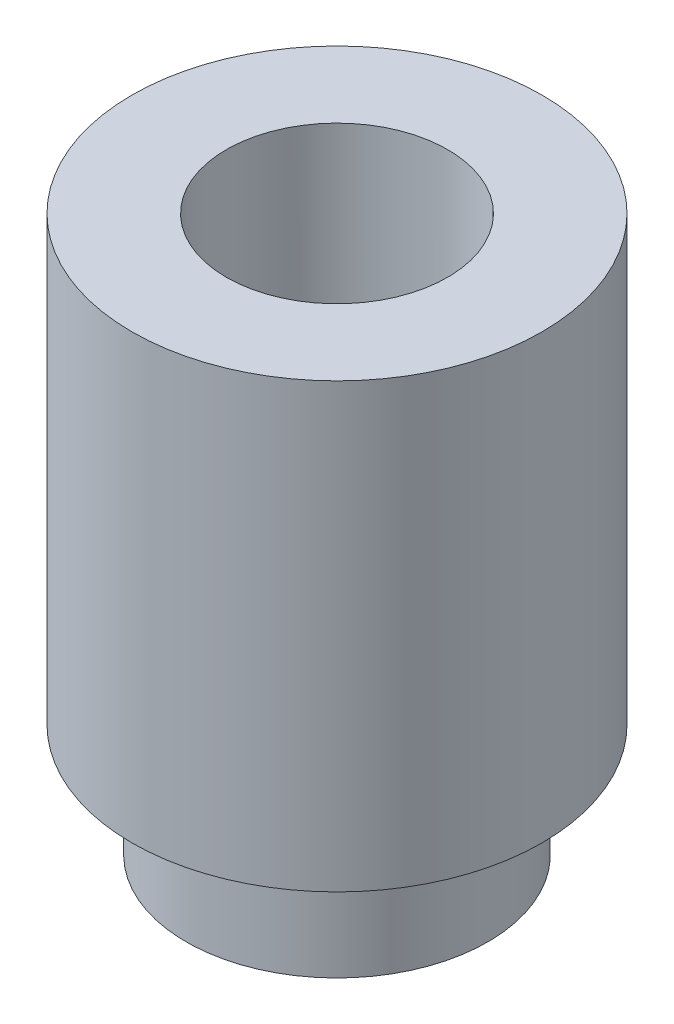
SolidWorks part; units mm, degrees
ref_plane "前视基准面" through (0, 0, 0) normal (0, 0, 1) x (1, 0, 0)
ref_plane "上视基准面" through (0, 0, 0) normal (0, 1, 0) x (1, 0, 0)
ref_plane "右视基准面" through (0, 0, 0) normal (1, 0, 0) x (0, 0, -1)
sketch "草图1" plane through (0, 0, 0) normal (0, 1, 0) x (1, 0, 0)
  circle A0 centre (0, 0) radius 2.78
  dimension "D1" = 5.56
extrude "凸台-拉伸1" add sketch "草图1" along normal blind 6
sketch "草图2" plane through (0, 0, 0) normal (0, -1, 0) x (1, 0, 0)
  circle A0 centre (0, 0) radius 2.045
  dimension "D1" = 4.09
extrude "凸台-拉伸2" add sketch "草图2" along normal blind 1.53
sketch "草图3" plane through (0, 6, 0) normal (0, 1, 0) x (1, 0, 0)
  circle A0 centre (0, 0) radius 1.5
  dimension "D1" = 3
extrude "切除-拉伸1" cut sketch "草图3" against normal up to next
